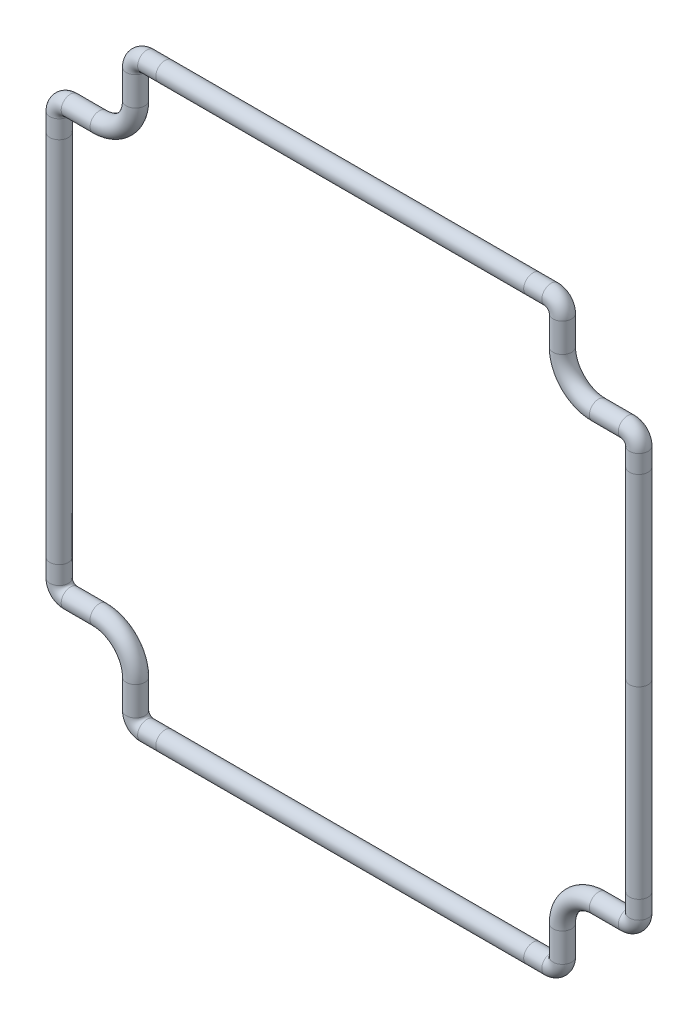
SolidWorks part; units mm, degrees
material "Rubber"
ref_plane "Front Plane" through (0, 0, 0) normal (0, 0, 1) x (1, 0, 0)
ref_plane "Top Plane" through (0, 0, 0) normal (0, 1, 0) x (1, 0, 0)
ref_plane "Right Plane" through (0, 0, 0) normal (1, 0, 0) x (0, 0, -1)
sketch "Sketch4" plane through (0, 0, 0) normal (0, 0, 1) x (1, 0, 0)
  line L20 (-14.9606, 19.5262) -> (-14.9606, 17.5006)
  line L21 (-12.8968, 20.32) -> (-14.1668, 20.32)
  line L22 (12.8969, 20.32) -> (-12.8968, 20.32)
  line L23 (14.1669, 20.32) -> (12.8969, 20.32)
  line L24 (14.9606, 17.5006) -> (14.9606, 19.5262)
  line L25 (19.5263, 14.9606) -> (17.5006, 14.9606)
  line L26 (20.32, 12.8968) -> (20.32, 14.1668)
  line L27 (20.32, -12.8969) -> (20.32, 12.8968)
  line L28 (20.32, -14.1669) -> (20.32, -12.8969)
  line L29 (17.5006, -14.9606) -> (19.5262, -14.9606)
  line L30 (14.9606, -19.5263) -> (14.9606, -17.5006)
  line L31 (12.8968, -20.32) -> (14.1668, -20.32)
  line L32 (-12.8969, -20.32) -> (12.8968, -20.32)
  line L33 (-14.1669, -20.32) -> (-12.8969, -20.32)
  line L34 (-14.9606, -17.5006) -> (-14.9606, -19.5262)
  line L35 (-19.5262, -14.9606) -> (-17.5006, -14.9606)
  line L36 (-20.32, -12.8968) -> (-20.32, -14.1668)
  line L37 (-20.32, 12.8969) -> (-20.32, -12.8968)
  line L38 (-20.32, 14.1669) -> (-20.32, 12.8969)
  line L39 (-17.5006, 14.9606) -> (-19.5262, 14.9606)
  arc A12 (-14.1668, 20.32) -> (-14.9606, 19.5262) centre (-14.1668, 19.5262) ccw
  arc A13 (14.9606, 19.5262) -> (14.1669, 20.32) centre (14.1669, 19.5262) ccw
  arc A14 (14.9606, 17.5006) -> (17.5006, 14.9606) centre (17.5006, 17.5006) ccw
  arc A15 (20.32, 14.1668) -> (19.5263, 14.9606) centre (19.5263, 14.1668) ccw
  arc A16 (19.5262, -14.9606) -> (20.32, -14.1669) centre (19.5262, -14.1669) ccw
  arc A17 (17.5006, -14.9606) -> (14.9606, -17.5006) centre (17.5006, -17.5006) ccw
  arc A18 (14.1668, -20.32) -> (14.9606, -19.5263) centre (14.1668, -19.5263) ccw
  arc A19 (-14.9606, -19.5262) -> (-14.1669, -20.32) centre (-14.1669, -19.5262) ccw
  arc A20 (-14.9606, -17.5006) -> (-17.5006, -14.9606) centre (-17.5006, -17.5006) ccw
  arc A21 (-20.32, -14.1668) -> (-19.5262, -14.9606) centre (-19.5262, -14.1668) ccw
  arc A22 (-19.5262, 14.9606) -> (-20.32, 14.1669) centre (-19.5262, 14.1669) ccw
  arc A23 (-17.5006, 14.9606) -> (-14.9606, 17.5006) centre (-17.5006, 17.5006) ccw
sketch "Sketch6" plane through (0, 0, 0) normal (0, 1, 0) x (1, 0, 0)
  circle A0 centre (20.32, 0) radius 0.65
  dimension "D1" = 1.3
sweep "Sweep2" add profiles "Sketch6" path "Sketch4"
